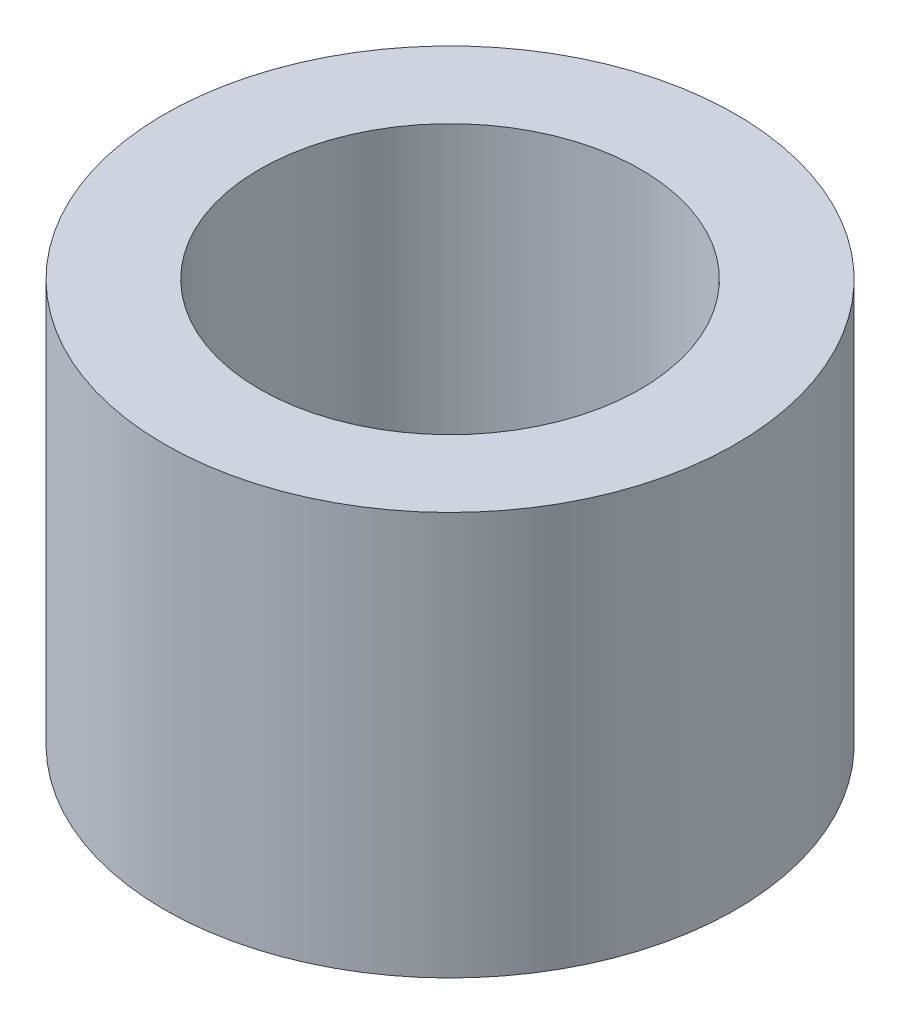
SolidWorks part; units mm, degrees
ref_plane "Front Plane" through (0, 0, 0) normal (0, 0, 1) x (1, 0, 0)
ref_plane "Top Plane" through (0, 0, 0) normal (0, 1, 0) x (1, 0, 0)
ref_plane "Right Plane" through (0, 0, 0) normal (1, 0, 0) x (0, 0, -1)
sketch "Sketch1" plane through (0, 0, 0) normal (0, 1, 0) x (1, 0, 0)
  circle A0 centre (0, 0) radius 6
  circle A1 centre (0, 0) radius 9
extrude "Boss-Extrude1" add sketch "Sketch1" along normal blind 12.7
